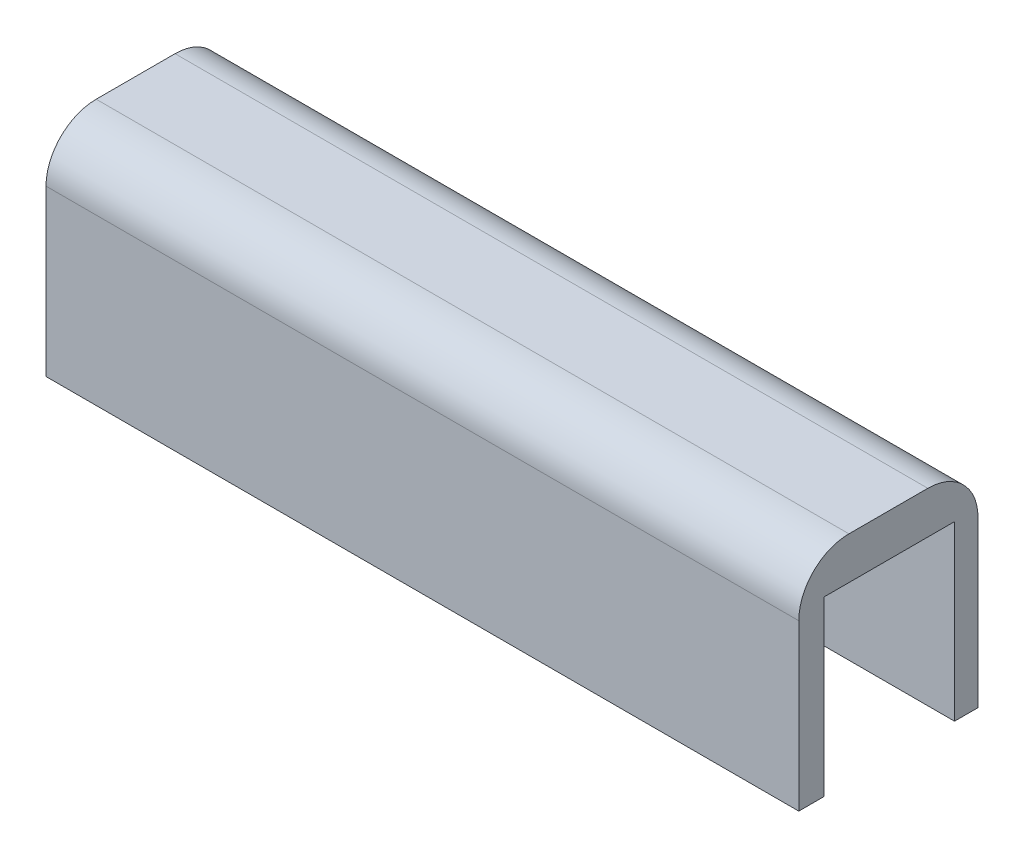
SolidWorks part; units mm, degrees
ref_plane "Front Plane" through (0, 0, 0) normal (0, 0, 1) x (1, 0, 0)
ref_plane "Top Plane" through (0, 0, 0) normal (0, 1, 0) x (1, 0, 0)
ref_plane "Right Plane" through (0, 0, 0) normal (1, 0, 0) x (0, 0, -1)
sketch "Sketch1" plane through (0, 0, 0) normal (1, 0, 0) x (0, 0, -1)
  line L0 (-15.6307, -4.5073) -> (-15.6307, 25.4927)
  line L1 (-15.6307, 25.4927) -> (9.3693, 25.4927)
  line L2 (9.3693, 25.4927) -> (9.3693, -4.5073)
  line L3 (9.3693, -4.5073) -> (6.0936, -4.5073)
  line L4 (6.0936, -4.5073) -> (6.0936, 19.6049)
  line L5 (6.0936, 19.6049) -> (-12.1307, 19.6049)
  line L6 (-12.1307, 19.6049) -> (-12.1307, -4.5073)
  line L7 (-12.1307, -4.5073) -> (-15.6307, -4.5073)
  dimension "D1" = 30
  dimension "D2" = 25
  dimension "D3" = 3.5
extrude "Boss-Extrude1" add sketch "Sketch1" along normal mid plane 105
fillet "Fillet1" radius 7 2 edges at (0, 25.4927, -9.3693) (0, 25.4927, 15.6307)
